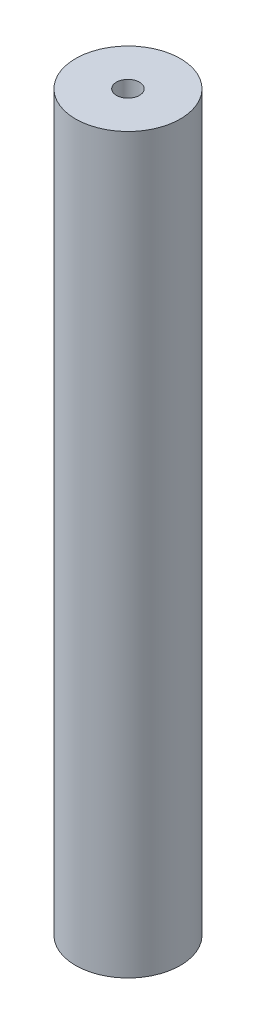
SolidWorks part; units mm, degrees
material "5052-H34"
ref_plane "正面" through (0, 0, 0) normal (0, 0, 1) x (1, 0, 0)
ref_plane "平面" through (0, 0, 0) normal (0, 1, 0) x (1, 0, 0)
ref_plane "右側面" through (0, 0, 0) normal (1, 0, 0) x (0, 0, -1)
sketch "ｽｹｯﾁ1" plane through (0, 0, 0) normal (0, 1, 0) x (1, 0, 0)
  circle A0 centre (0, 0) radius 7.5
  dimension "D1" = 15
extrude "ﾎﾞｽ - 押し出し1" add sketch "ｽｹｯﾁ1" along normal blind 105
hole_wizard "M4x0.7 ねじ穴1" positions "ｽｹｯﾁ2" profile "ｽｹｯﾁ3" tap size "M4x0.7" standard "JIS"
sketch "ｽｹｯﾁ2" plane through (0, 105, 0) normal (0, 1, 0) x (1, 0, 0)
  point P0 (0, 0)
sketch "ｽｹｯﾁ3" plane through (0, 105, 0) normal (1, 0, 0) x (0, 0, 1)
  line L0 (0, 0) -> (0, 20.9914)
  line L1 (0, 20.9914) -> (1.65, 20)
  line L2 (1.65, 20) -> (1.65, 0)
  line L5 (1.65, 0) -> (0, 0)
  line L10 (0, 20.9914) -> (-1.65, 20) construction
  line L11 (0, -6.35) -> (0, 107.95) construction
  dimension "ねじ下穴ﾄﾞﾘﾙ直径" = 3.3
  dimension "ねじ下穴ﾄﾞﾘﾙの深さ" = 20
  dimension "ﾄﾞﾘﾙ角度" = 118
ref_plane "平面1" through (0, 52.5, 0) normal (0, 1, 0) x (1, 0, 0)
mirror "ﾐﾗｰ1" about plane through (0, 52.5, 0) normal (0, 1, 0) of "M4x0.7 ねじ穴1"
